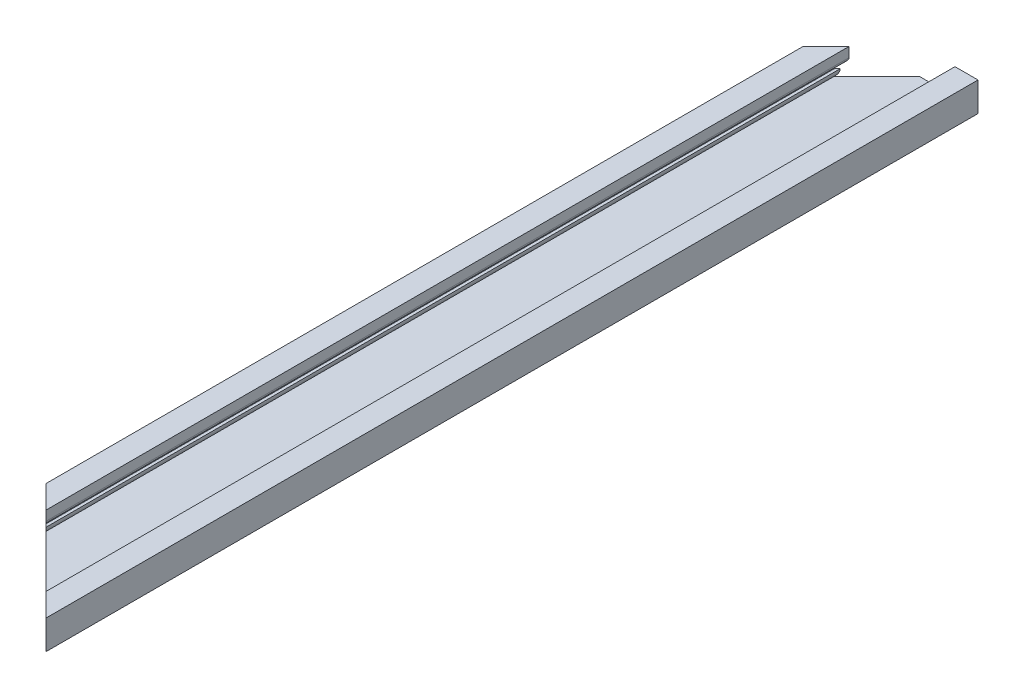
SolidWorks part; units mm, degrees
ref_plane "정면" through (0, 0, 0) normal (0, 0, 1) x (1, 0, 0)
ref_plane "윗면" through (0, 0, 0) normal (0, 1, 0) x (1, 0, 0)
ref_plane "우측면" through (0, 0, 0) normal (1, 0, 0) x (0, 0, -1)
sketch "스케치1" plane through (0, 0, 0) normal (0, 0, 1) x (1, 0, 0)
  line L1 (-30, 7.5) -> (30, 7.5)
  line L2 (-30, 7.5) -> (-30, -7.5)
  line L3 (-30, -7.5) -> (30, -7.5)
  line L4 (30, 7.5) -> (30, -7.5)
  line L5 (-30, 7.5) -> (30, -7.5) construction
  line L6 (-30, -7.5) -> (30, 7.5) construction
  point P0 (0, 0)
  dimension "D1" = 60
  dimension "D2" = 15
extrude "보스-돌출1" add sketch "스케치1" along normal blind 510
sketch "스케치2" plane through (0, 0, 0) normal (0, 0, -1) x (-1, 0, 0)
  line L0 (30, -7.5) -> (-30, -7.5) construction
  line L2 (-30, -7.5) -> (-30, 7.5) construction
  line L3 (30, 7.5) -> (30, -7.5) construction
  circle A0 centre (-25, -2.5) radius 3
  circle A1 centre (25, -2.5) radius 3
  dimension "D1" = 6
  dimension "D3" = 5
  dimension "D4" = 6
  dimension "D6" = 5
  dimension "D2" = 5
  dimension "D5" = 5
extrude "컷-돌출1" cut sketch "스케치2" against normal through all
sketch "스케치3" plane through (0, 0, 0) normal (0, 0, -1) x (-1, 0, 0)
  line L0 (-22.1716, -6) -> (22.1716, -6)
  line L1 (-20.5, -2.5) -> (-25, -2.5)
  line L2 (-25, -2.5) -> (-25, 0.5)
  line L3 (-25, 0.5) -> (25, 0.5)
  line L4 (25, 0.5) -> (25, -2.5)
  line L5 (25, -2.5) -> (20.5, -2.5)
  line L6 (30, -7.5) -> (-30, -7.5) construction
  arc A0 (22.1716, -6) -> (20.5, -2.5) centre (25, -2.5) cw
  arc A1 (-22.1716, -6) -> (-20.5, -2.5) centre (-25, -2.5) ccw
  circle A2 centre (-25, -2.5) radius 3 construction
  circle A3 centre (25, -2.5) radius 3 construction
  dimension "D2" = 1.5
  dimension "D1" = 1.5
  dimension "1.5" = 1.5
extrude "컷-돌출2" cut sketch "스케치3" against normal through all
sketch "스케치4" plane through (0, 0, 0) normal (0, 0, -1) x (-1, 0, 0)
  line L0 (-18.1431, 0.5) -> (18.1569, 0.5)
  line L1 (25, 0.5) -> (-25, 0.5) construction
  line L2 (-18.1431, 0.5) -> (-18.1431, 7.5)
  line L3 (-30, 7.5) -> (30, 7.5) construction
  line L4 (-18.1431, 7.5) -> (18.1569, 7.5)
  line L5 (18.1569, 7.5) -> (18.1569, 0.5)
  point P5 (0, 0)
  dimension "D1" = 36.3
extrude "컷-돌출3" cut sketch "스케치4" against normal through all
fillet "필렛1" radius 2 2 edges at (-18.1569, 0.5, 255) (18.1431, 0.5, 255)
sketch "스케치5" plane through (0, -7.5, 0) normal (0, -1, 0) x (1, 0, 0)
  line L0 (-30, 510) -> (-30, 450)
  line L1 (-30, 510) -> (-30, 0) construction
  line L2 (-30, 450) -> (30, 510)
  line L5 (-30, 0) -> (30, 0)
  line L6 (-30, 255) -> (30, 255) construction
  line L7 (30, 510) -> (30, 0) construction
  line L15 (-30, 510) -> (30, 510)
  line L17 (-30, 60) -> (30, 0)
  line L18 (-30, 0) -> (-30, 60)
  dimension "D1" = 45
extrude "컷-돌출4" cut sketch "스케치5" against normal through all
sketch "스케치7" plane through (0, -7.5, 0) normal (0, -1, 0) x (1, 0, 0)
  line L1 (30, 0) -> (0, 0)
  line L2 (30, 0) -> (30, 30)
  line L3 (30, 30) -> (0, 30)
  line L4 (0, 0) -> (0, 30)
  dimension "D1" = 30
  dimension "D2" = 30
extrude "컷-돌출6" cut sketch "스케치7" against normal through all and the other way through all
